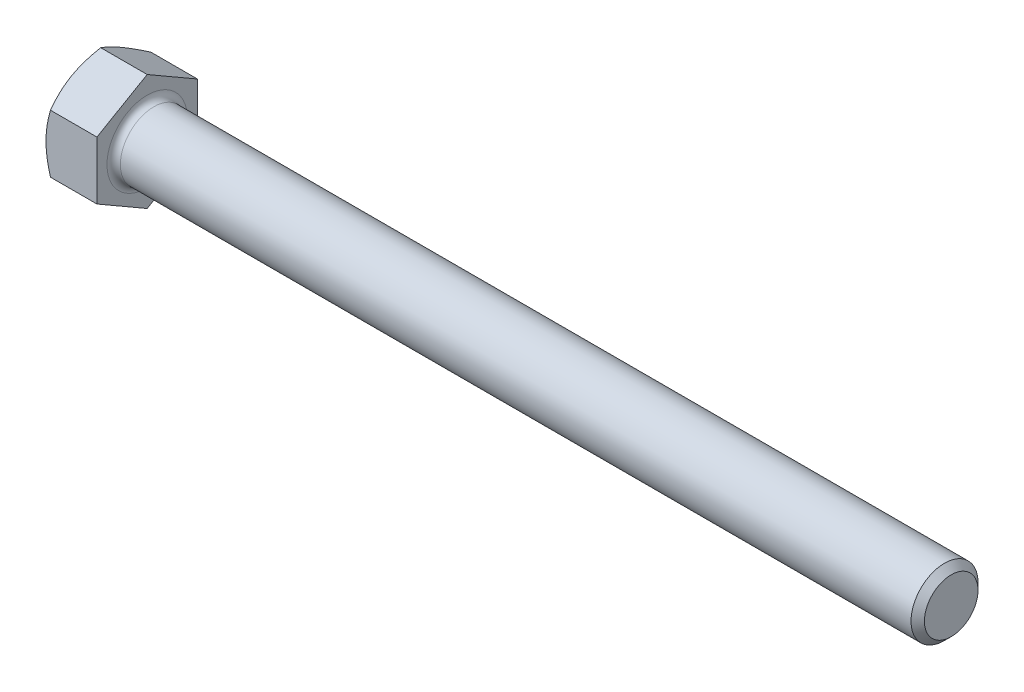
SolidWorks part; units mm, degrees
ref_plane "Front Plane" through (0, 0, 0) normal (0, 0, 1) x (1, 0, 0)
ref_plane "Top Plane" through (0, 0, 0) normal (0, 1, 0) x (1, 0, 0)
ref_plane "Right Plane" through (0, 0, 0) normal (1, 0, 0) x (0, 0, -1)
ref_plane "Plane1"
sketch "Sketch1" plane through (0, 0, 0) normal (0, 0, 1) x (1, 0, 0)
  line L0 (76.2, 0) -> (76.2, 3.175)
  line L1 (76.2, 3.175) -> (0, 3.175)
  line L2 (0, 3.175) -> (0, 0)
  line L3 (0, 0) -> (76.2, 0)
  line L4 (76.2, 0) -> (0, 0) construction
  dimension "D1" = 90
  dimension "D2" = 76.2
revolve "Body" add sketch "Sketch1" angle 360 about L4
cosmetic thread "Cosmetic Thread1" parameters "D1"=38.1, "D2"=4.8387
sketch "Sketch2" plane through (0, 0, 0) normal (-1, 0, 0) x (0, 0, 1)
  line L0 (0, 5.4993) -> (4.7625, 2.7496)
  line L1 (4.7625, 2.7496) -> (4.7625, -2.7496)
  line L2 (4.7625, -2.7496) -> (0, -5.4993)
  line L3 (0, -5.4993) -> (-4.7625, -2.7496)
  line L4 (-4.7625, -2.7496) -> (-4.7625, 2.7496)
  line L5 (-4.7625, 2.7496) -> (0, 5.4993)
  dimension "D1" = 9.525
extrude "Head" add sketch "Sketch2" along normal blind 4.826
ref_plane "Plane2"
sketch "Sketch3" plane through (0, 0, 0) normal (0, 0, 1) x (1, 0, 0)
  line L0 (-4.826, 4.7625) -> (-4.2761, 5.715)
  line L1 (-4.2761, 5.715) -> (-4.826, 5.715)
  line L2 (-4.826, 5.715) -> (-4.826, 4.7625)
  line L3 (-1.1, 0) -> (-0.234, 0) construction
  line L5 (0, 2.7496) -> (0, 5.4993) construction
  dimension "D1" = 60
  dimension "D2" = 60
  dimension "D3" = 30
revolve "Thread" cut sketch "Sketch3" angle 360 about L3
chamfer "Chamfer2" distance 0.635 distance2 0.6351 1 edges at (76.2, 3.175, 0)
fillet "Fillet" radius 0.635 1 edges at (0, 3.175, 0)
